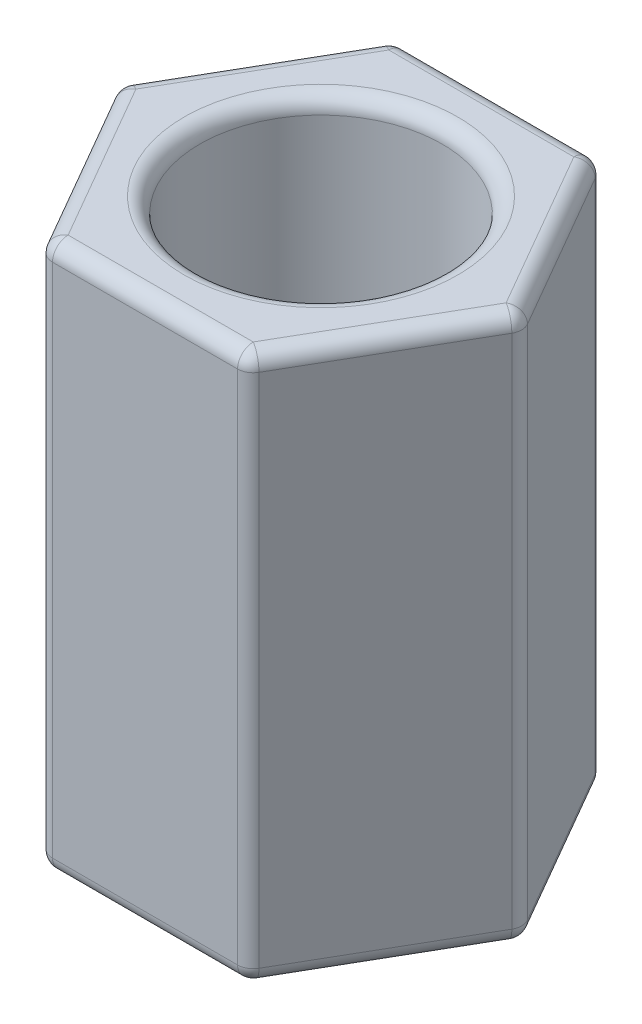
SolidWorks part; units mm, degrees
ref_plane "Front Plane" through (0, 0, 0) normal (0, 0, 1) x (1, 0, 0)
ref_plane "Top Plane" through (0, 0, 0) normal (0, 1, 0) x (1, 0, 0)
ref_plane "Right Plane" through (0, 0, 0) normal (1, 0, 0) x (0, 0, -1)
sketch "Sketch1" plane through (0, 0, 0) normal (0, 1, 0) x (1, 0, 0)
  line L0 (0, 2.25) -> (1.299, 0)
  line L1 (1.299, 0) -> (3.8971, 0)
  line L2 (3.8971, 0) -> (5.1962, 2.25)
  line L3 (5.1962, 2.25) -> (3.8971, 4.5)
  line L4 (3.8971, 4.5) -> (1.299, 4.5)
  line L5 (1.299, 4.5) -> (0, 2.25)
  line L6 (0, 2.25) -> (5.1962, 2.25) construction
  line L7 (2.5981, 4.5) -> (2.5981, 0) construction
  circle A0 centre (2.5981, 2.25) radius 1.55
  point P9 (2.5981, 2.25)
  dimension "D3" = 3.1
  dimension "D1" = 120
  dimension "D2" = 4.5
extrude "Boss-Extrude1" add sketch "Sketch1" along normal blind 7 contours L4 L5 L0 L1 L2 L3 A0
fillet "Fillet1" radius 0.2 20 edges at (3.8971, 3.5, -4.5) (2.5981, 7, -4.5) (1.299, 3.5, -4.5) (2.5981, 0, -4.5) (2.5981, 7, -0.7) (2.5981, 0, -0.7) (4.5466, 0, -3.375) (4.5466, 0, -1.125) (2.5981, 0, 0) (0.6495, 0, -1.125) (0.6495, 0, -3.375) (0, 3.5, -2.25) (5.1962, 3.5, -2.25) (3.8971, 3.5, 0) (1.299, 3.5, 0) (0.6495, 7, -1.125) (0.6495, 7, -3.375) (4.5466, 7, -3.375) (4.5466, 7, -1.125) (2.5981, 7, 0)
